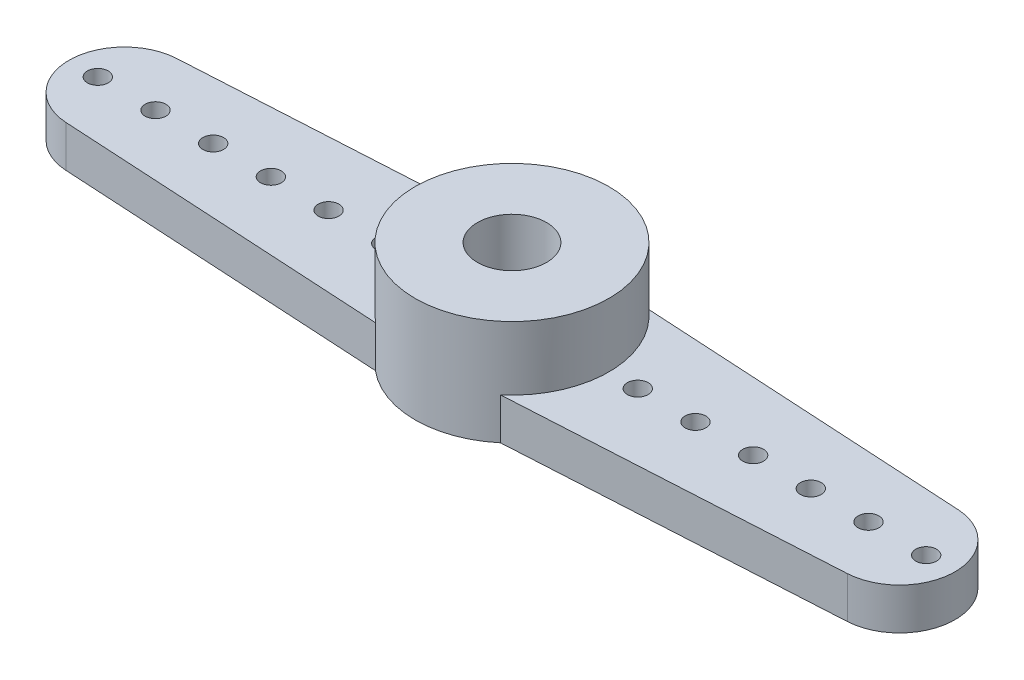
SolidWorks part; units mm, degrees
ref_plane "Front Plane" through (0, 0, 0) normal (0, 0, 1) x (1, 0, 0)
ref_plane "Top Plane" through (0, 0, 0) normal (0, 1, 0) x (1, 0, 0)
ref_plane "Right Plane" through (0, 0, 0) normal (1, 0, 0) x (0, 0, -1)
sketch "Sketch1" plane through (0, 0, 0) normal (0, 1, 0) x (1, 0, 0)
  line L0 (2.2571, 2.675) -> (14.1106, 2)
  line L1 (0, 0) -> (13.9968, 0) construction
  line L2 (14.1106, -2) -> (2.2571, -2.675)
  line L3 (0, 3.5) -> (0, -3.5) construction
  arc A0 (2.2571, 2.675) -> (2.2571, -2.675) centre (0, 0) ccw
  arc A1 (14.1106, 2) -> (14.1106, -2) centre (13.9968, 0) cw
  point P11 (-3.5, 0)
  point P12 (16, 0)
  dimension "D1" = 4
  dimension "D2" = 7
  dimension "D3" = 5.35
  dimension "D4" = 19.5
extrude "Boss-Extrude1" add sketch "Sketch1" along normal blind 1.5
sketch "Sketch2" plane through (0, 1.5, 0) normal (0, 1, 0) x (1, 0, 0)
  circle A0 centre (0, 0) radius 3.5
  arc A1 (2.2571, 2.675) -> (2.2571, -2.675) centre (0, 0) ccw construction
extrude "Boss-Extrude2" add sketch "Sketch2" along normal offset from surface (2.3 mm away) 3.8 up to face at (7.2169, 0, 0)
sketch "Sketch3" plane through (0, 1.5, 0) normal (0, 1, 0) x (1, 0, 0)
  line L0 (16, 0) -> (13.9167, 0) construction
  line L1 (13.9167, 0) -> (11.8333, 0) construction
  line L2 (11.8333, 0) -> (9.75, 0) construction
  line L3 (9.75, 0) -> (7.6667, 0) construction
  line L4 (7.6667, 0) -> (5.5833, 0) construction
  line L5 (5.5833, 0) -> (3.5, 0) construction
  arc A0 (14.1106, -2) -> (14.1106, 2) centre (13.9968, 0) ccw construction
  circle A1 centre (14.9583, 0) radius 0.375
  circle A2 centre (12.875, 0) radius 0.375
  circle A3 centre (10.7917, 0) radius 0.375
  circle A4 centre (8.7083, 0) radius 0.375
  circle A5 centre (6.625, 0) radius 0.375
  circle A6 centre (4.5417, 0) radius 0.375
  arc A7 (2.2571, -2.675) -> (2.2571, 2.675) centre (0, 0) ccw construction
  circle A8 centre (0, 0) radius 1.25
  point P40 (10.7917, 0)
  dimension "D1" = 0.75
  dimension "D3" = 2.5
  dimension "D2" = 6
extrude "Cut-Extrude1" cut sketch "Sketch3" against normal through all both and the other way through all
mirror "Mirror1" about plane through (0, 0, 0) normal (1, 0, 0) of "Cut-Extrude1", "Boss-Extrude1"
